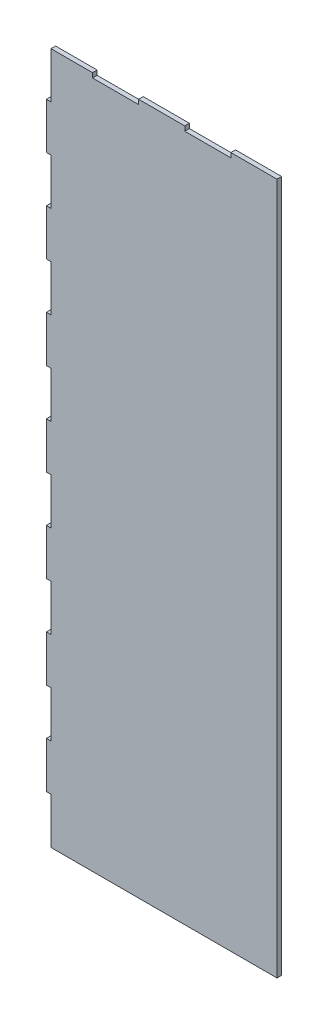
SolidWorks part; units mm, degrees
material "Contreplaqué pin"
ref_plane "Plan de face" through (0, 0, 0) normal (0, 0, 1) x (1, 0, 0)
ref_plane "Plan de dessus" through (0, 0, 0) normal (0, 1, 0) x (1, 0, 0)
ref_plane "Plan de droite" through (0, 0, 0) normal (1, 0, 0) x (0, 0, -1)
sketch "Esquisse1" plane through (0, 0, 0) normal (0, 0, 1) x (1, 0, 0)
  line L0 (0, 0) -> (0, 50)
  line L5 (0, 50) -> (-5, 50)
  line L6 (-5, 50) -> (-5, 100)
  line L7 (-5, 100) -> (0, 100)
  line L8 (0, 100) -> (0, 150)
  line L9 (0, 150) -> (-5, 150)
  line L10 (-5, 150) -> (-5, 200)
  line L11 (-5, 200) -> (0, 200)
  line L12 (0, 200) -> (0, 250)
  line L13 (0, 250) -> (-5, 250)
  line L14 (-5, 250) -> (-5, 300)
  line L15 (-5, 300) -> (0, 300)
  line L16 (0, 300) -> (0, 350)
  line L17 (0, 350) -> (-5, 350)
  line L18 (-5, 350) -> (-5, 400)
  line L19 (-5, 400) -> (0, 400)
  line L20 (0, 400) -> (0, 450)
  line L21 (0, 450) -> (-5, 450)
  line L22 (-5, 450) -> (-5, 500)
  line L23 (-5, 500) -> (0, 500)
  line L24 (0, 500) -> (0, 550)
  line L25 (0, 550) -> (-5, 550)
  line L26 (-5, 550) -> (-5, 600)
  line L27 (-5, 600) -> (0, 600)
  line L28 (0, 600) -> (0, 650)
  line L29 (0, 650) -> (-5, 650)
  line L30 (-5, 650) -> (-5, 700)
  line L31 (-5, 700) -> (0, 700)
  line L32 (0, 700) -> (0, 750)
  line L33 (0, 750) -> (45, 750)
  line L34 (45, 750) -> (45, 745)
  line L35 (45, 745) -> (95, 745)
  line L36 (95, 745) -> (95, 750)
  line L37 (95, 750) -> (145, 750)
  line L38 (145, 750) -> (145, 745)
  line L39 (145, 745) -> (195, 745)
  line L40 (195, 745) -> (195, 750)
  line L41 (195, 750) -> (245, 750)
  line L42 (245, 750) -> (245, 0)
  line L43 (245, 0) -> (0, 0)
  dimension "D1" = 750
  dimension "D2" = 250
  dimension "D3" = 50
  dimension "D4" = 50
  dimension "D5" = 50
  dimension "D6" = 50
  dimension "D7" = 5
  dimension "D8" = 50
  dimension "D9" = 45
  dimension "D10" = 5
extrude "Boss.-Extru.1" add sketch "Esquisse1" along normal blind 5
